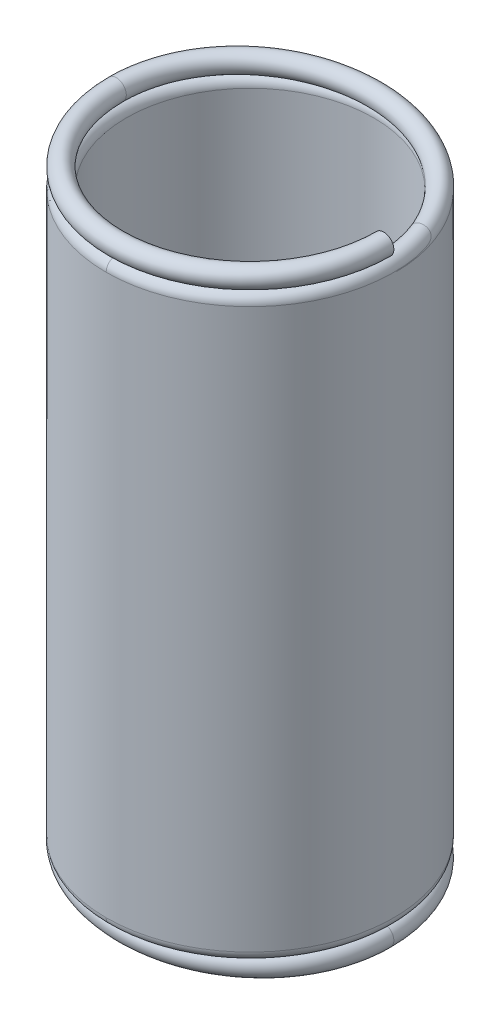
SolidWorks part; units mm, degrees
ref_plane "Front Plane" through (0, 0, 0) normal (0, 0, 1) x (1, 0, 0)
ref_plane "Top Plane" through (0, 0, 0) normal (0, 1, 0) x (1, 0, 0)
ref_plane "Right Plane" through (0, 0, 0) normal (1, 0, 0) x (0, 0, -1)
ref_plane "Plane1" through (0, 0, 0) normal (0, 0, 1) x (1, 0, 0)
sketch "Sketch1" plane through (0, 0, 0) normal (0, 0, 1) x (1, 0, 0)
  line L0 (4, 9.035) -> (4, -9.035)
  line L1 (4.65, -9.035) -> (4.65, 9.035)
  line L2 (0, -50) -> (0, 50) construction
  arc A0 (4, -9.035) -> (4.65, -9.035) centre (4.325, -9.035) ccw
  arc A1 (4.65, 9.035) -> (4, 9.035) centre (4.325, 9.035) ccw
revolve "Revolve1" add sketch "Sketch1" angle 360 about L2
ref_plane "Plane2" through (0, 0, 0) normal (0, 0, 1) x (1, 0, 0)
sketch "Sketch2" plane through (0, 0, 0) normal (0, 0, 1) x (1, 0, 0)
  line L0 (0.33, 13.67) -> (-0.33, 5.02) construction
  circle A0 centre (-4.325, 9.675) radius 0.325
revolve "Revolve2" add sketch "Sketch2" angle 180 about L0
ref_plane "Plane3" through (0, 0, 0) normal (0, 0, 1) x (1, 0, 0)
sketch "Sketch3" plane through (0, 0, 0) normal (0, 0, 1) x (1, 0, 0)
  line L0 (0, 50) -> (0, -50) construction
  circle A0 centre (-4.325, 9.675) radius 0.325
revolve "Revolve3" add sketch "Sketch3" angle 180 about L0
ref_plane "Plane4" through (0, 0, 0) normal (0, 0, 1) x (1, 0, 0)
sketch "Sketch4" plane through (0, 0, 0) normal (0, 0, 1) x (1, 0, 0)
  line L0 (-0.33, -13.67) -> (0.33, -5.02) construction
  circle A0 centre (4.325, -9.675) radius 0.325
revolve "Revolve4" add sketch "Sketch4" angle 180 about L0
ref_plane "Plane5" through (0, 0, 0) normal (0, 0, 1) x (1, 0, 0)
sketch "Sketch5" plane through (0, 0, 0) normal (0, 0, 1) x (1, 0, 0)
  line L0 (0, -50) -> (0, 50) construction
  circle A0 centre (4.325, -9.675) radius 0.325
revolve "Revolve5" add sketch "Sketch5" angle 180 about L0
